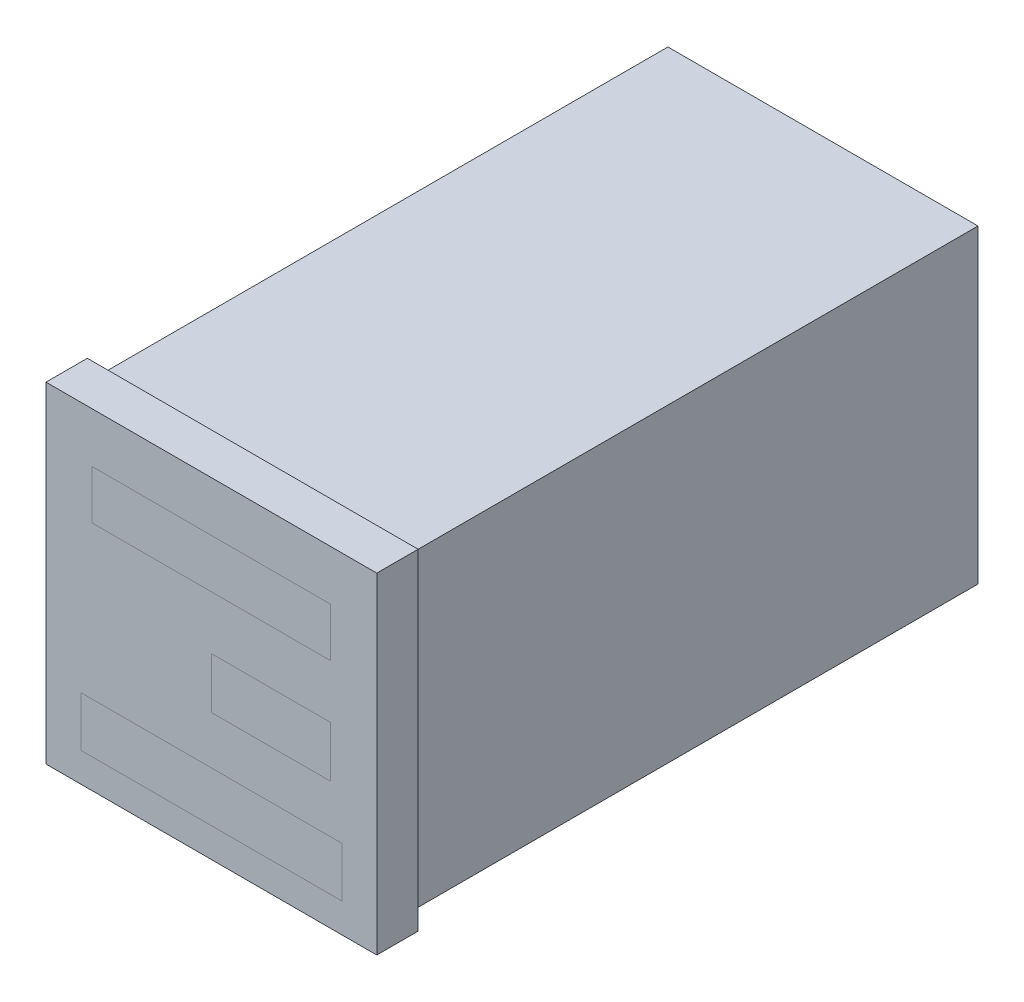
SolidWorks part; units mm, degrees
ref_plane "Front Plane" through (0, 0, 0) normal (0, 0, 1) x (1, 0, 0)
ref_plane "Top Plane" through (0, 0, 0) normal (0, 1, 0) x (1, 0, 0)
ref_plane "Right Plane" through (0, 0, 0) normal (1, 0, 0) x (0, 0, -1)
sketch "Sketch1" plane through (0, 0, 0) normal (0, 0, 1) x (1, 0, 0)
  line L1 (-24, -24) -> (24, -24)
  line L2 (-24, -24) -> (-24, 24)
  line L3 (-24, 24) -> (24, 24)
  line L4 (24, -24) -> (24, 24)
  line L5 (-24, -24) -> (24, 24) construction
  line L6 (-24, 24) -> (24, -24) construction
  point P0 (0, 0)
  dimension "D1" = 48
  dimension "D2" = 48
extrude "Boss-Extrude1" add sketch "Sketch1" against normal blind 6
sketch "Sketch2" plane through (0, 0, -6) normal (0, 0, -1) x (-1, 0, 0)
  line L1 (-22.5, -22.5) -> (22.5, -22.5)
  line L2 (-22.5, -22.5) -> (-22.5, 22.5)
  line L3 (-22.5, 22.5) -> (22.5, 22.5)
  line L4 (22.5, -22.5) -> (22.5, 22.5)
  line L5 (-22.5, -22.5) -> (22.5, 22.5) construction
  line L6 (-22.5, 22.5) -> (22.5, -22.5) construction
  point P0 (0, 0)
  dimension "D1" = 45
  dimension "D2" = 45
extrude "Boss-Extrude2" add sketch "Sketch2" along normal blind 82.75
sketch "Sketch3" plane through (0, 0, 0) normal (0, 0, 1) x (1, 0, 0)
  line L1 (-17.3086, 16.7369) -> (17.3086, 16.7369)
  line L2 (-17.3086, 16.7369) -> (-17.3086, 9.6497)
  line L3 (-17.3086, 9.6497) -> (17.3086, 9.6497)
  line L4 (17.3086, 16.7369) -> (17.3086, 9.6497)
  line L5 (-17.3086, 16.7369) -> (17.3086, 9.6497) construction
  line L6 (-17.3086, 9.6497) -> (17.3086, 16.7369) construction
  line L7 (0.0241, 1.8834) -> (17.3086, 1.8834)
  line L8 (0.0241, 1.8834) -> (0.0241, -5.5143)
  line L9 (0.0241, -5.5143) -> (17.3086, -5.5143)
  line L10 (17.3086, 1.8834) -> (17.3086, -5.5143)
  line L11 (0.0241, 1.8834) -> (17.3086, -5.5143) construction
  line L12 (0.0241, -5.5143) -> (17.3086, 1.8834) construction
  line L13 (-18.9322, -12.4835) -> (18.9803, -12.4835)
  line L14 (-18.9322, -12.4835) -> (-18.9322, -19.7391)
  line L15 (-18.9322, -19.7391) -> (18.9803, -19.7391)
  line L16 (18.9803, -12.4835) -> (18.9803, -19.7391)
  line L17 (-18.9322, -12.4835) -> (18.9803, -19.7391) construction
  line L18 (-18.9322, -19.7391) -> (18.9803, -12.4835) construction
  point P0 (0, 13.1933)
  point P5 (8.6663, -1.8155)
  point P10 (0.0241, -16.1113)
split line "Split Line1"
